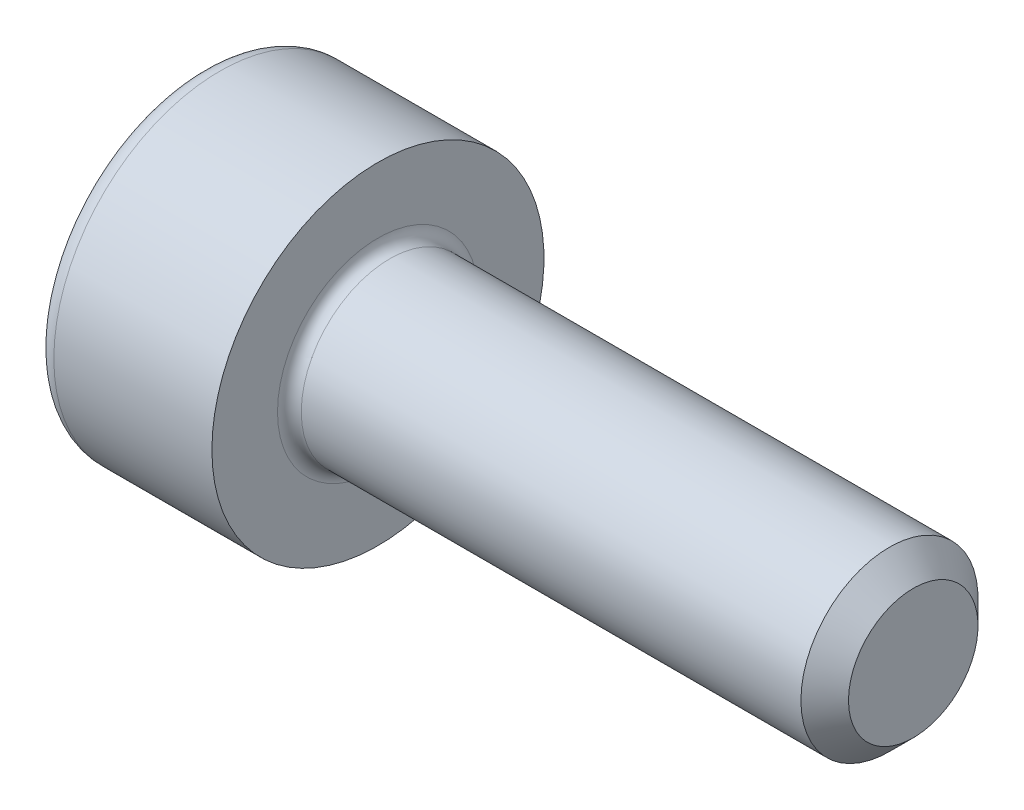
SolidWorks part; units mm, degrees
ref_plane "Спереди" through (0, 0, 0) normal (0, 0, 1) x (1, 0, 0)
ref_plane "Сверху" through (0, 0, 0) normal (0, 1, 0) x (1, 0, 0)
ref_plane "Справа" through (0, 0, 0) normal (1, 0, 0) x (0, 0, -1)
sketch "Sketch1" plane through (0, 0, 0) normal (0, 0, 1) x (1, 0, 0)
  line L0 (0, 0) -> (1.4887, 0)
  line L1 (1.4887, 0) -> (1.4887, 1.3957)
  line L2 (1.4887, 1.3957) -> (0, 1.3957)
  line L3 (0, 1.3957) -> (0, 0)
  line L4 (1.4887, 0) -> (5.9887, 0)
  line L5 (5.9887, 0) -> (5.9887, 0.7444)
  line L6 (5.9887, 0.7444) -> (1.4887, 0.7444)
  dimension "D1" = 4.5
revolve "Revolve1" add sketch "Sketch1" angle 360 about L0
fillet "Fillet1" radius 0.1 1 edges at (1.4887, 0, 0.7444)
fillet "Fillet2" radius 0.16 1 edges at (0, 0, 1.3957)
chamfer "Chamfer1" distance 0.2 angle 45 1 edges at (5.9887, 0, 0.7444)
sketch "Sketch2" plane through (0, 0, 0) normal (-1, 0, 0) x (0, 0, 1)
  line L1 (0, 0.8776) -> (-0.76, 0.4388)
  line L2 (-0.76, 0.4388) -> (-0.76, -0.4388)
  line L3 (-0.76, -0.4388) -> (0, -0.8776)
  line L4 (0, -0.8776) -> (0.76, -0.4388)
  line L5 (0.76, -0.4388) -> (0.76, 0.4388)
  line L6 (0.76, 0.4388) -> (0, 0.8776)
  circle A0 centre (0, 0) radius 0.76 construction
extrude "Extrude1" cut sketch "Sketch2" against normal blind 0.7
